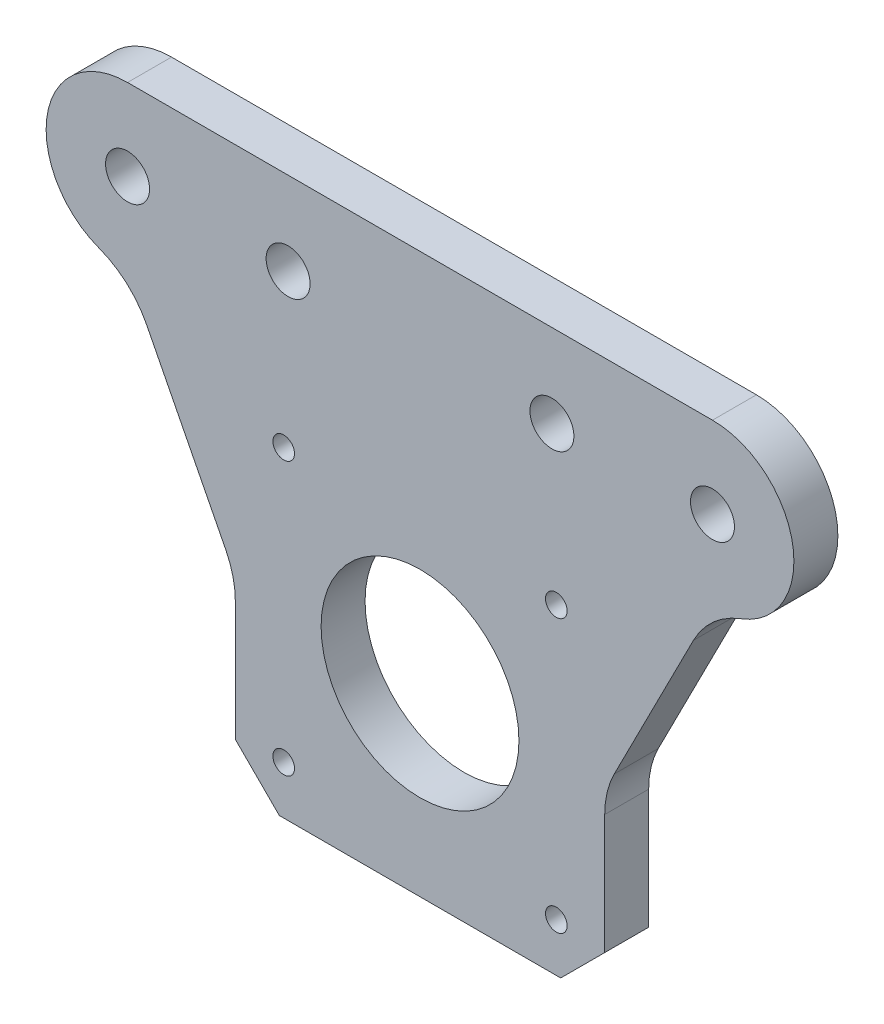
SolidWorks part; units mm, degrees
material "Plastique personnalisé"
ref_plane "Plan de face" through (0, 0, 0) normal (0, 0, 1) x (1, 0, 0)
ref_plane "Plan de dessus" through (0, 0, 0) normal (0, 1, 0) x (1, 0, 0)
ref_plane "Plan de droite" through (0, 0, 0) normal (1, 0, 0) x (0, 0, -1)
sketch "Esquisse1" plane through (0, 0, 0) normal (0, 0, 1) x (1, 0, 0)
  line L0 (0, 0) -> (0, 21) construction
  line L1 (0, 0) -> (0, -21) construction
  line L2 (0, 0) -> (21, 0) construction
  line L3 (0, 0) -> (-21, 0) construction
  line L4 (-21, 0) -> (-21, 21) construction
  line L5 (-21, 21) -> (21, 21) construction
  line L6 (21, 21) -> (21, -21) construction
  line L7 (21, -21) -> (-21, -21) construction
  line L8 (-21, -21) -> (-21, 0) construction
  line L9 (0, 0) -> (-35.9116, 35.9633) construction
  line L10 (-35.9116, 35.9633) -> (-42.5037, 42.5649) construction
  line L11 (-42.5037, 42.5649) -> (42.4963, 42.5649) construction
  line L12 (0, 0) -> (42.4963, 42.5649) construction
  line L13 (33.2583, 33.3062) -> (33.2583, 42.5649) construction
  line L14 (-33.2583, 42.5649) -> (33.2583, 42.5649)
  line L18 (-33.2583, 33.3062) -> (-33.2583, 42.5649) construction
  line L19 (33.2583, 33.3062) -> (33.2583, 24.0459) construction
  line L20 (33.2583, 24.0459) -> (21, 0)
  line L21 (21, 0) -> (21, -21)
  line L22 (21, -21) -> (-21, -21)
  line L23 (-21, 0) -> (-21, -21)
  line L24 (-33.2583, 24.0459) -> (-21, 0)
  line L25 (0, 33.1084) -> (-15, 33.1084) construction
  line L26 (0, 33.1084) -> (33.2583, 33.3054) construction
  circle A0 centre (0, 0) radius 7.4873
  circle A3 centre (-33.2583, 33.3062) radius 2.5
  circle A4 centre (33.2583, 33.3062) radius 2.5
  arc A11 (33.2583, 42.5649) -> (33.2583, 24.0459) centre (33.2583, 33.3054) cw
  arc A12 (-33.2583, 42.5649) -> (-33.2583, 24.0459) centre (-33.2583, 33.3054) ccw
  circle A13 centre (-15, 33.1084) radius 2.5
  circle A14 centre (15, 33.1084) radius 2.5
  dimension "D1" = 21
  dimension "D2" = 9.2587
  dimension "D4" = 15
  dimension "D3" = 85
extrude "Boss.-Extru.1" add sketch "Esquisse1" along normal blind 5
sketch "Esquisse2" plane through (0, 0, 5) normal (0, 0, 1) x (1, 0, 0)
  circle A0 centre (-15.5, 15.5) radius 1.2295
  circle A1 centre (15.5, 15.5) radius 1.2295
  circle A2 centre (-15.5, -15.5) radius 1.2295
  circle A3 centre (15.5, -15.5) radius 1.2295
extrude "Enlèv. mat.-Extru.1" cut sketch "Esquisse2" against normal blind 5
fillet "Congé2" radius 10 2 edges at (-21, 0, 2.5) (21, 0, 2.5)
fillet "Congé3" radius 10 2 edges at (-33.2583, 24.0459, 2.5) (33.2583, 24.0459, 2.5)
sketch "Esquisse3" plane through (0, 0, 5) normal (0, 0, 1) x (1, 0, 0)
  circle A0 centre (0, 0) radius 11.25
  dimension "D1" = 22.5
extrude "Enlèv. mat.-Extru.2" cut sketch "Esquisse3" against normal blind 10
chamfer "Chanfrein1" distance 5 angle 45 2 edges at (21, -21, 2.5) (-21, -21, 2.5)
